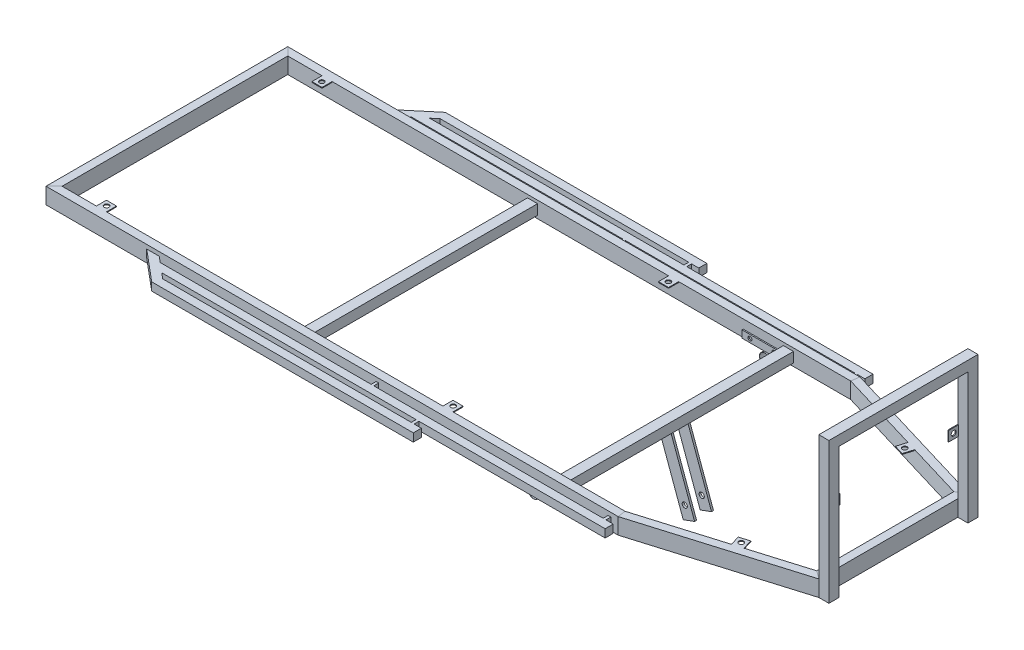
SolidWorks part; units mm, degrees
ref_plane "Front Plane" through (0, 0, 0) normal (0, 0, 1) x (1, 0, 0)
ref_plane "Top Plane" through (0, 0, 0) normal (0, 1, 0) x (1, 0, 0)
ref_plane "Right Plane" through (0, 0, 0) normal (1, 0, 0) x (0, 0, -1)
sketch "Sketch1" plane through (0, 0, 0) normal (0, 1, 0) x (1, 0, 0)
  line L0 (0, 0) -> (0, 600)
  line L1 (0, 600) -> (1420, 600)
  line L2 (1420, 600) -> (1803, 485)
  line L3 (1803, 485) -> (1803, 115)
  line L4 (1803, 115) -> (1420, 0)
  line L5 (1420, 0) -> (0, 0)
  line L6 (0, 300) -> (2057.5916, 300) construction
  dimension "D1" = 600
  dimension "D2" = 1803
  dimension "D3" = 370
  dimension "D4" = 1420
ref_plane "Plane1" through (0, 0, -600) normal (0, 0, -1) x (-1, 0, 0)
sketch "Sketch2" plane through (0, 0, -600) normal (0, 0, -1) x (-1, 0, 0)
  line L0 (-19, 1) -> (-19, 39)
  line L1 (0, 0) -> (-20, 0)
  line L2 (0, 0) -> (0, 40)
  line L3 (0, 40) -> (-20, 40)
  line L4 (-20, 0) -> (-20, 40)
  line L5 (-1, 39) -> (-19, 39)
  line L6 (-1, 1) -> (-1, 39)
  line L7 (-1, 1) -> (-19, 1)
  dimension "D1" = 40
  dimension "D2" = 20
  dimension "D3" = 1
sweep "Sweep1" add profiles "Sketch2" path "Sketch1"
sketch "Sketch3" plane through (0, 0, -580) normal (0, 0, 1) x (1, 0, 0)
  line L1 (0, 20) -> (1803, 20) construction
  line L2 (0, 0) -> (0, 40) construction
  line L3 (1803, 0) -> (1803, 40) construction
  line L6 (615, 32.5) -> (640, 32.5)
  line L7 (615, 32.5) -> (615, 7.5)
  line L8 (615, 7.5) -> (640, 7.5)
  line L9 (640, 32.5) -> (640, 7.5)
  line L10 (615, 32.5) -> (640, 7.5) construction
  line L11 (615, 7.5) -> (640, 32.5) construction
  point P6 (627.5, 20)
  dimension "D1" = 25
  dimension "D2" = 640
extrude "Extrude-Thin1" add sketch "Sketch3" along normal up to next thin
sketch "Sketch4" plane through (0, 0, -580) normal (0, 0, 1) x (1, 0, 0)
  line L0 (0, 20) -> (1803, 20) construction
  line L1 (0, 0) -> (0, 40) construction
  line L2 (1803, 0) -> (1803, 40) construction
  line L3 (1250, 31.5) -> (1274, 31.5)
  line L4 (1250, 32.5) -> (1275, 32.5)
  line L5 (1250, 32.5) -> (1250, 31.5)
  line L6 (1274, 7.5) -> (1275, 7.5)
  line L7 (1275, 32.5) -> (1275, 7.5)
  line L8 (615, 32.5) -> (615, 7.5) construction
  line L10 (1274, 31.5) -> (1274, 7.5)
  circle A0 centre (1261.5, 20) radius 12.5 construction
  dimension "D1" = 25
  dimension "D2" = 25
  dimension "D3" = 25
  dimension "D4" = 1
  dimension "D5" = 1
  dimension "D6" = 660
extrude "Boss-Extrude1" add sketch "Sketch4" along normal up to next
sketch "Sketch5" plane through (0, 0, -580) normal (0, 0, 1) x (1, 0, 0)
  circle A0 centre (1262, 19.5) radius 12
  dimension "D1" = 24
sketch "Sketch6" plane through (1803, 0, 0) normal (1, 0, 0) x (0, 0, -1)
  line L0 (460, 25) -> (460, 325)
  line L1 (115, 0) -> (140, 0)
  line L2 (115, 0) -> (115, 350)
  line L3 (115, 350) -> (485, 350)
  line L4 (485, 0) -> (485, 350)
  line L5 (140, 325) -> (460, 325)
  line L6 (140, 25) -> (140, 325)
  line L7 (140, 25) -> (140, 0)
  line L8 (140, 25) -> (460, 25) construction
  line L9 (460, 25) -> (460, 0)
  line L10 (460, 0) -> (485, 0)
  line L11 (115, 0) -> (485, 0) construction
  dimension "D1" = 350
  dimension "D2" = 25
extrude "Boss-Extrude5" add sketch "Sketch6" along normal blind 25 separate body
ref_plane "Plane2" through (0, 20, 0) normal (0, -1, 0) x (-1, 0, 0)
sketch "Sketch7" plane through (0, 20, 0) normal (0, -1, 0) x (-1, 0, 0)
  line L0 (-250, 600) -> (-326.6044, 664.2788)
  line L1 (-1420, 600) -> (0, 600) construction
  line L2 (0, 600) -> (0, 0) construction
  line L3 (-281.1145, 600) -> (-357.7189, 664.2788)
  line L4 (-262.8558, 584.6791) -> (-339.4602, 648.9579) construction
  line L5 (-326.6044, 664.2788) -> (-357.7189, 664.2788)
  line L6 (-250, 600) -> (-281.1145, 600)
  dimension "D1" = 100
  dimension "D2" = 250
  dimension "D4" = 40
  dimension "D3" = 20
extrude "Boss-Extrude6" add sketch "Sketch7" along normal mid plane 20
sketch "Sketch8" plane through (0, 30, 0) normal (0, 1, 0) x (1, 0, 0)
  line L0 (357.7189, 664.2788) -> (975.8014, 664.2788)
  line L1 (975.8014, 664.2788) -> (975.8014, 644.2788)
  line L2 (975.8014, 644.2788) -> (333.8838, 644.2788)
  line L3 (357.7189, 664.2788) -> (281.1145, 600) construction
  line L4 (333.8838, 644.2788) -> (357.7189, 664.2788)
  line L5 (295.7477, 612.2788) -> (1420, 612.2788)
  line L6 (1420, 612.2788) -> (1420, 632.2788)
  line L7 (1420, 632.2788) -> (319.5828, 632.2788)
  line L8 (319.5828, 632.2788) -> (295.7477, 612.2788)
  point P3 (345.8014, 654.2788)
  point P8 (975.8014, 654.2788)
  dimension "D1" = 630
  dimension "D2" = 20
  dimension "D3" = 20
  dimension "D4" = 12
extrude "Boss-Extrude7" add sketch "Sketch8" against normal blind 20
sketch "Sketch10" plane through (0, 30, 0) normal (0, 1, 0) x (1, 0, 0)
  line L0 (1420, 632.2788) -> (319.5828, 632.2788) construction
  line L1 (950.8014, 632.2788) -> (957.8014, 632.2788)
  line L2 (950.8014, 632.2788) -> (950.8014, 644.2788)
  line L3 (950.8014, 644.2788) -> (957.8014, 644.2788)
  line L4 (957.8014, 632.2788) -> (957.8014, 644.2788)
  line L5 (333.8838, 644.2788) -> (975.8014, 644.2788) construction
  line L6 (975.8014, 644.2788) -> (975.8014, 664.2788) construction
  line L7 (1420, 600) -> (0, 600) construction
  line L8 (1395, 600) -> (1402, 600)
  line L9 (1395, 600) -> (1395, 612.2788)
  line L10 (1395, 612.2788) -> (1402, 612.2788)
  line L11 (1402, 600) -> (1402, 612.2788)
  line L12 (295.7477, 612.2788) -> (1420, 612.2788) construction
  line L13 (1420, 612.2788) -> (1420, 632.2788) construction
  line L14 (295.7477, 612.2788) -> (1420, 612.2788) construction
  line L15 (819.3014, 612.2788) -> (825.8014, 612.2788)
  line L16 (819.3014, 612.2788) -> (819.3014, 600)
  line L17 (819.3014, 600) -> (825.8014, 600)
  line L18 (825.8014, 612.2788) -> (825.8014, 600)
  line L19 (1420, 600) -> (0, 600) construction
  line L20 (975.8014, 644.2788) -> (975.8014, 664.2788) construction
  dimension "D1" = 7
  dimension "D2" = 18
  dimension "D3" = 18
  dimension "D4" = 6.5
  dimension "D5" = 150
extrude "Boss-Extrude8" add sketch "Sketch10" against normal up to surface (20 mm away)
ref_plane "Plane3" through (0, 0, -300) normal (0, 0, 1) x (1, 0, 0)
mirror "Mirror2" about plane through (0, 0, -300) normal (0, 0, 1) of bodies 106 107 109 108 110 112 111
sketch "Sketch11" plane through (0, 40, 0) normal (0, 1, 0) x (1, 0, 0)
  line L1 (20, 20) -> (1417.0622, 20) construction
  line L2 (615, 20) -> (615, 580) construction
  line L3 (1417.0622, 20) -> (1783, 129.8769) construction
  line L4 (20, 300) -> (1783, 300) construction
  line L6 (20, 580) -> (20, 20) construction
  line L7 (1783, 129.8769) -> (1783, 470.1231) construction
  point P10 (117.5, 45)
  line B0 (105, 20) -> (130, 20)
  line B1 (105, 20) -> (105, 45)
  line B2 (105, 45) -> (130, 45)
  line B3 (130, 20) -> (130, 45)
  circle B4 centre (117.5, 33) radius 6
  line B5 (965, 20) -> (990, 20)
  line B6 (965, 20) -> (965, 45)
  line B7 (965, 45) -> (990, 45)
  line B8 (990, 20) -> (990, 45)
  circle B9 centre (977.5, 33) radius 6
  line B10 (1620.1812, 80.9888) -> (1644.1252, 88.1782)
  line B11 (1620.1812, 80.9888) -> (1612.9918, 104.9327)
  line B12 (1612.9918, 104.9327) -> (1636.9357, 112.1221)
  line B13 (1644.1252, 88.1782) -> (1636.9357, 112.1221)
  circle B14 centre (1628.4147, 97.0343) radius 6
  line B15 (965, 580) -> (990, 580)
  line B16 (965, 580) -> (965, 555)
  line B17 (965, 555) -> (990, 555)
  line B18 (990, 580) -> (990, 555)
  circle B19 centre (977.5, 567) radius 6
  line B20 (105, 580) -> (130, 580)
  line B21 (105, 580) -> (105, 555)
  line B22 (105, 555) -> (130, 555)
  line B23 (130, 580) -> (130, 555)
  circle B24 centre (117.5, 567) radius 6
  line B25 (1620.1812, 519.0112) -> (1644.1252, 511.8218)
  line B26 (1620.1812, 519.0112) -> (1612.9918, 495.0673)
  line B27 (1612.9918, 495.0673) -> (1636.9357, 487.8779)
  line B28 (1644.1252, 511.8218) -> (1636.9357, 487.8779)
  circle B29 centre (1628.4147, 502.9657) radius 6
  dimension "D1" = 375
  dimension "D2" = 170
sketch_block_instance "Block1-1"
sketch_block "Block1" parameters "D2"=12, "D1"=25, "D3"=12
sketch_block_instance "Block1-2"
sketch_block_instance "Block1-4"
sketch_block_instance "Block1-6"
sketch_block_instance "Block1-7"
sketch_block_instance "Block1-8"
extrude "Boss-Extrude9" add sketch "Sketch11" against normal blind 2
sketch "Sketch12" plane through (1803, 0, 0) normal (-1, 0, 0) x (0, 0, 1)
  line L0 (-460, 325) -> (-460, 0) construction
  line L1 (-485, 350) -> (-115, 350) construction
  line L2 (-300, 325) -> (-300, -113.1123) construction
  line L3 (-140, 325) -> (-460, 325) construction
  line B0 (-460, 175) -> (-435, 175)
  line B1 (-460, 175) -> (-460, 200)
  line B2 (-460, 200) -> (-435, 200)
  line B3 (-435, 175) -> (-435, 200)
  circle B4 centre (-447.5, 188) radius 6
  line B5 (-140, 175) -> (-165, 175)
  line B6 (-140, 175) -> (-140, 200)
  line B7 (-140, 200) -> (-165, 200)
  line B8 (-165, 175) -> (-165, 200)
  circle B9 centre (-152.5, 188) radius 6
  dimension "D1" = 150
sketch_block_instance "Block1-9"
sketch_block_instance "Block1-11"
extrude "Boss-Extrude10" add sketch "Sketch12" against normal blind 2
sketch "Sketch14" plane through (0, 0, -300) normal (0, 0, 1) x (1, 0, 0)
  line L2 (1274.4937, 14.5) -> (1242, 14.5)
  line L4 (1242, 14.5) -> (1271.9756, -155.5)
  line L5 (1271.9756, -155.5) -> (1303.4894, -149.9433)
  line L6 (1275, 32.5) -> (1250, 32.5) construction
  line L8 (1303.4894, -149.9433) -> (1274.4937, 14.5)
  dimension "D1" = 32
  dimension "D2" = 170
  dimension "D3" = 18
  dimension "D4" = 80
ref_plane "Plane4" through (0, 0, -282) normal (0, 0, 1) x (1, 0, 0)
sketch "Sketch18" plane through (0, 0, -20) normal (0, 0, -1) x (-1, 0, 0)
  line L0 (-1420, 0) -> (0, 0) construction
  line L1 (-1250, 0) -> (-1150, 0)
  line L2 (-1250, 0) -> (-1250, 18)
  line L3 (-1250, 18) -> (-1150, 18)
  line L4 (-1150, 0) -> (-1150, 18)
  line L5 (-1250, 9) -> (-1150, 9) construction
  line L6 (-1200, 18) -> (-1200, 0) construction
  circle A1 centre (-1230, 9) radius 5
  circle A2 centre (-1170, 9) radius 5
  dimension "D3" = 10
  dimension "D4" = 60
  dimension "D1" = 100
  dimension "D2" = 18
extrude "Boss-Extrude14" add sketch "Sketch18" along normal blind 3 separate body
sketch "Sketch20" plane through (0, 0, -23) normal (0, 0, -1) x (-1, 0, 0)
  line L0 (-1250, 18) -> (-1250, 0) construction
  line L1 (-1420, 40) -> (0, 40) construction
  circle A0 centre (-1210, -13.5) radius 13
  circle A1 centre (-1210, -13.5) radius 13.5
  dimension "D1" = 26
  dimension "D2" = 27
  dimension "D4" = 53.5
  dimension "D3" = 40
extrude "Boss-Extrude15" add sketch "Sketch20" along normal blind 3 and the other way blind 23 separate body
ref_plane "Plane5" through (0, 0, -300) normal (0, 0, 1) x (1, 0, 0)
mirror "Mirror7" about plane through (0, 0, -300) normal (0, 0, 1) of bodies 126 129
ref_plane "Plane6" through (0, 0, -276.5) normal (0, 0, 1) x (1, 0, 0)
sketch "Sketch22" plane through (0, 0, -276.5) normal (0, 0, 1) x (1, 0, 0)
  line L0 (1275, 7.5) -> (1333.1404, -152.2394)
  line L1 (1333.1404, -152.2394) -> (1304.9496, -162.5)
  line L2 (1304.9496, -162.5) -> (1243.0747, 7.5)
  line L3 (1243.0747, 7.5) -> (1275, 7.5)
  line L4 (1319.045, -157.3697) -> (1308.7844, -129.1789) construction
  circle A0 centre (1308.7844, -129.1789) radius 6.5
  dimension "D4" = 13
  dimension "D1" = 30
  dimension "D2" = 170
  dimension "D3" = 70
  dimension "D5" = 30
extrude "Boss-Extrude16" add sketch "Sketch22" against normal blind 5
mirror "Mirror8" about plane through (0, 0, -300) normal (0, 0, 1) of "Boss-Extrude16"
extrude "Boss-Extrude18" add sketch "Sketch5" along normal up to next separate body contours A0
